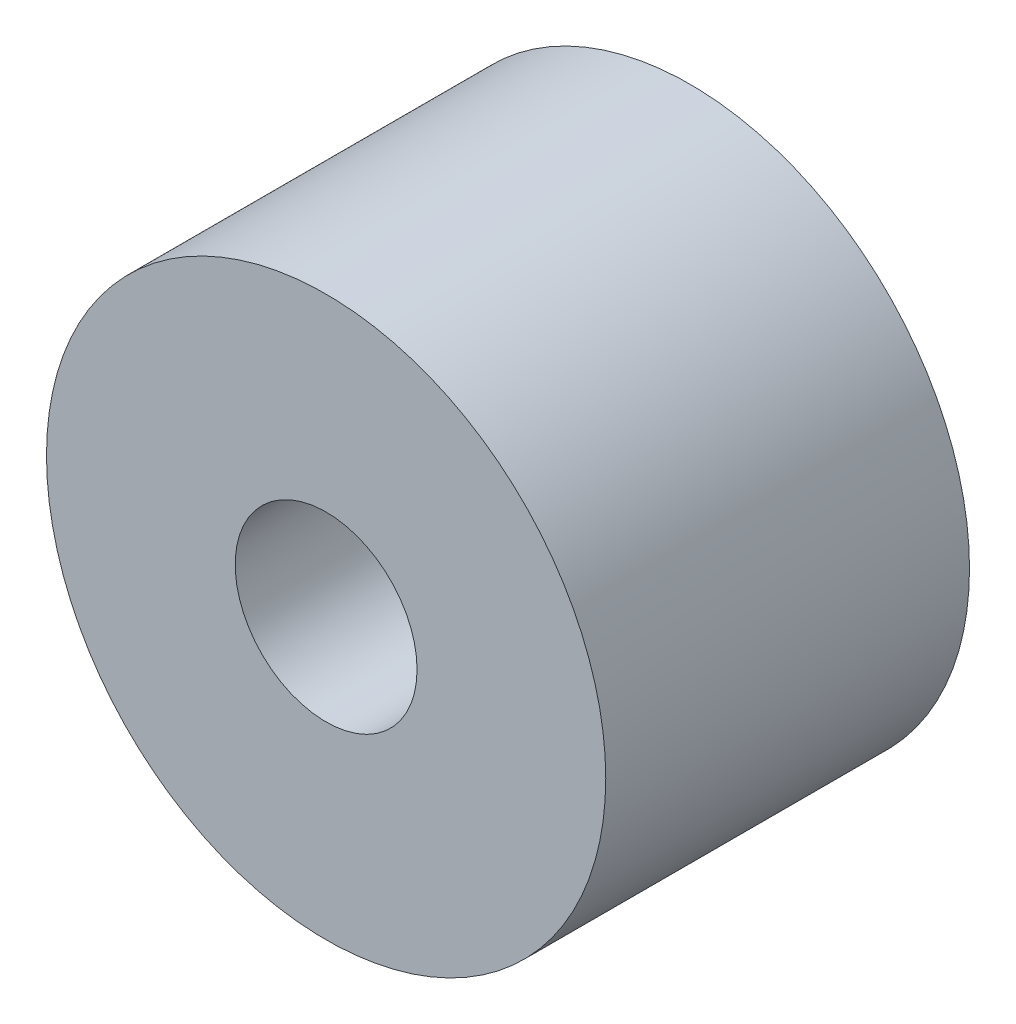
SolidWorks part; units mm, degrees
ref_plane "Front" through (0, 0, 0) normal (0, 0, 1) x (1, 0, 0)
ref_plane "Top" through (0, 0, 0) normal (0, 1, 0) x (1, 0, 0)
ref_plane "Right" through (0, 0, 0) normal (1, 0, 0) x (0, 0, -1)
sketch "Sketch1" plane through (0, 0, 0) normal (0, 0, 1) x (1, 0, 0)
  circle A0 centre (0, 0) radius 6.15
extrude "Boss-Extrude1" add sketch "Sketch1" along normal blind 8
sketch "Sketch2" plane through (0, 0, 8) normal (0, 0, 1) x (1, 0, 0)
  circle A0 centre (0, 0) radius 2
extrude "Cut-Extrude1" cut sketch "Sketch2" against normal through all
